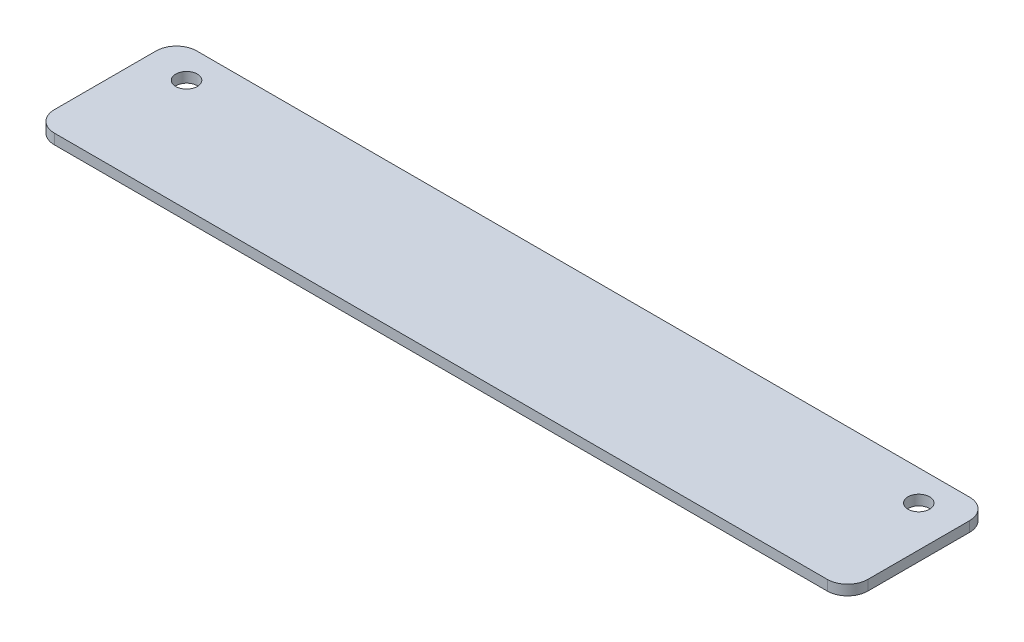
SolidWorks part; units mm, degrees
ref_plane "Front Plane" through (0, 0, 0) normal (0, 0, 1) x (1, 0, 0)
ref_plane "Top Plane" through (0, 0, 0) normal (0, 1, 0) x (1, 0, 0)
ref_plane "Right Plane" through (0, 0, 0) normal (1, 0, 0) x (0, 0, -1)
sketch "Sketch1" plane through (0, 0, 0) normal (0, 1, 0) x (1, 0, 0)
  line L1 (0, 0) -> (254, 0)
  line L2 (0, 0) -> (0, 44.45)
  line L3 (0, 44.45) -> (254, 44.45)
  line L4 (254, 0) -> (254, 44.45)
  dimension "D1" = 254
  dimension "D2" = 44.45
extrude "Boss-Extrude1" add sketch "Sketch1" along normal blind 3.175
fillet "Fillet1" radius 6.35 4 edges at (0, 1.5875, -44.45) (254, 1.5875, -44.45) (254, 1.5875, 0) (0, 1.5875, 0)
hole_wizard "17/64 (0.26563) Diameter Hole1" positions "Sketch2" profile "Sketch3" hole size "17/64" standard "ANSI Inch" end condition through all
sketch "Sketch2" plane through (0, 3.175, 0) normal (0, 1, 0) x (1, 0, 0)
  line L0 (0, 38.1) -> (0, 6.35) construction
  line L1 (254, 6.35) -> (254, 38.1) construction
  line L2 (247.65, 44.45) -> (6.35, 44.45) construction
  point P0 (12.7, 34.925)
  point P2 (241.3, 34.925)
  dimension "D1" = 12.7
  dimension "D2" = 12.7
  dimension "D3" = 9.525
sketch "Sketch3" plane through (12.7, 3.175, -34.925) normal (1, 0, 0) x (0, 0, 1)
  line L0 (0, 0) -> (0, 3.175)
  line L1 (0, 3.175) -> (3.3735, 3.175)
  line L2 (3.3735, 3.175) -> (3.3735, 0)
  line L5 (3.3735, 0) -> (0, 0)
  line L11 (0, -6.35) -> (0, 107.95) construction
  dimension "Thru Hole Dia." = 6.747
  dimension "Thru Hole Depth" = 3.175
